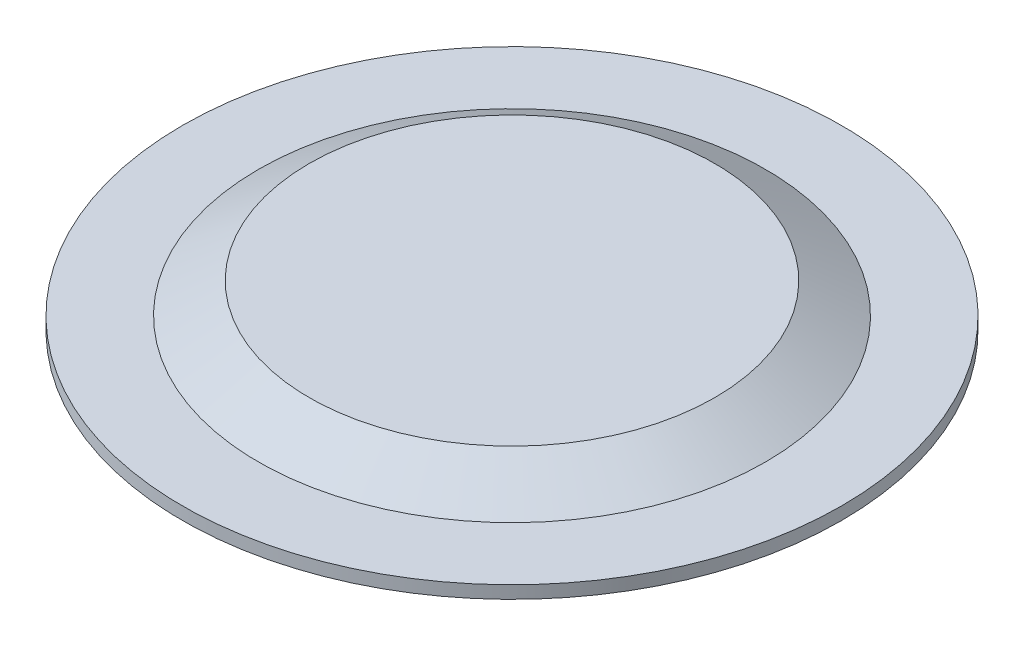
SolidWorks part; units mm, degrees
material "Rubber"
ref_plane "Front Plane" through (0, 0, 0) normal (0, 0, 1) x (1, 0, 0)
ref_plane "Top Plane" through (0, 0, 0) normal (0, 1, 0) x (1, 0, 0)
ref_plane "Right Plane" through (0, 0, 0) normal (1, 0, 0) x (0, 0, -1)
sketch "Sketch1" plane through (0, 0, 0) normal (0, 0, 1) x (1, 0, 0)
  line L0 (0, 0) -> (0, 2.159) construction
  line L1 (-16.51, 0) -> (-12.5241, 0)
  line L2 (-12.5241, 0) -> (-9.9841, 1.524)
  line L3 (-9.9841, 1.524) -> (0, 1.524)
  line L4 (0, 1.524) -> (0, 2.159)
  line L5 (0, 2.159) -> (-10.16, 2.159)
  line L6 (-10.16, 2.159) -> (-12.7, 0.635)
  line L7 (-12.7, 0.635) -> (-16.51, 0.635)
  line L8 (-16.51, 0.635) -> (-16.51, 0)
  dimension "D1" = 33.02
  dimension "D2" = 0.635
  dimension "D3" = 1.524
  dimension "D4" = 25.4
  dimension "D5" = 20.32
  dimension "D6" = 0.635
revolve "Revolve1" add sketch "Sketch1" angle 360 about L0
